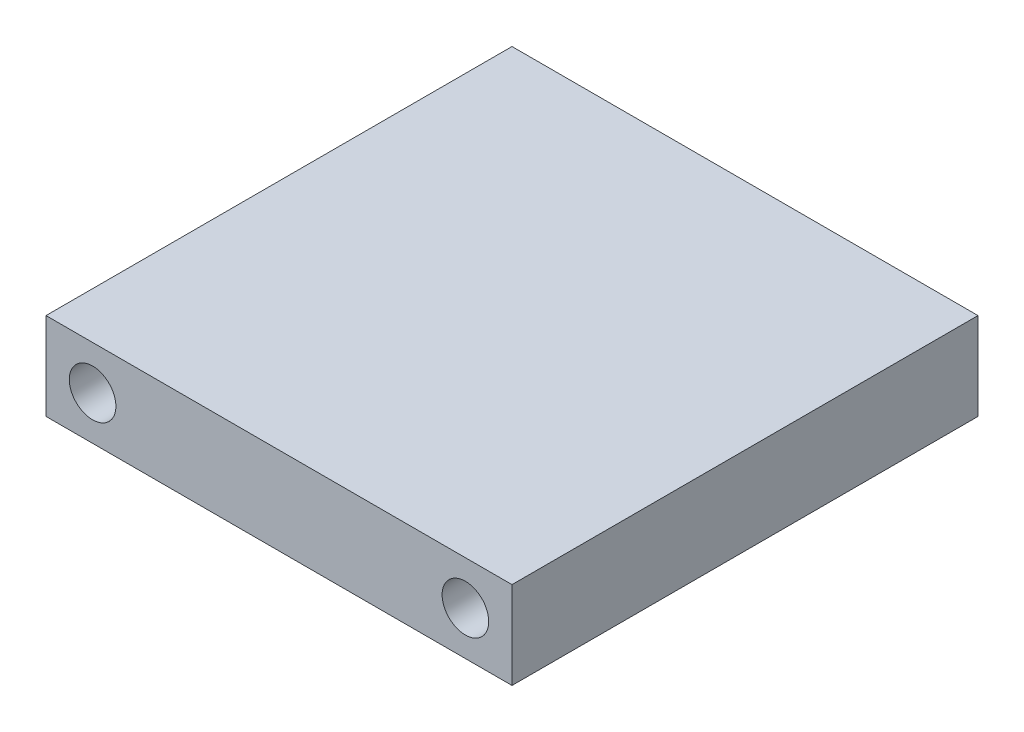
SolidWorks part; units mm, degrees
ref_plane "Front Plane" through (0, 0, 0) normal (0, 0, 1) x (1, 0, 0)
ref_plane "Top Plane" through (0, 0, 0) normal (0, 1, 0) x (1, 0, 0)
ref_plane "Right Plane" through (0, 0, 0) normal (1, 0, 0) x (0, 0, -1)
sketch "Sketch2" plane through (0, 0, 0) normal (0, 1, 0) x (1, 0, 0)
  line L1 (-25.4, 25.4) -> (25.4, 25.4)
  line L2 (-25.4, 25.4) -> (-25.4, -25.4)
  line L3 (-25.4, -25.4) -> (25.4, -25.4)
  line L4 (25.4, 25.4) -> (25.4, -25.4)
  line L5 (-25.4, 25.4) -> (25.4, -25.4) construction
  line L6 (-25.4, -25.4) -> (25.4, 25.4) construction
  point P0 (0, 0)
  dimension "D1" = 50.8
  dimension "D2" = 50.8
extrude "Boss-Extrude1" add sketch "Sketch2" along normal blind 9.525 contours L2 L3 L4 L1
sketch "Sketch3" plane through (0, 0, 25.4) normal (0, 0, 1) x (1, 0, 0)
  line L0 (25.4, 9.525) -> (25.4, 0) construction
  line L1 (-25.4, 9.525) -> (-25.4, 0) construction
  circle A0 centre (20.32, 4.7625) radius 2.54
  circle A1 centre (-20.32, 4.7625) radius 2.54
  point P7 (25.4, 4.7625)
  dimension "D3" = 5.08
  dimension "D1" = 5.08
  dimension "D2" = 5.08
hole_wizard "#6-32 Tapped Hole1" positions "Sketch4" profile "Sketch5" tap size "#6-32" standard "ANSI Inch"
sketch "Sketch4" plane through (0, 0, 25.4) normal (0, 0, 1) x (1, 0, 0)
  circle A0 centre (-20.32, 4.7625) radius 2.54 construction
  circle A1 centre (20.32, 4.7625) radius 2.54 construction
  point P0 (-20.32, 4.7625)
  point P2 (20.32, 4.7625)
sketch "Sketch5" plane through (-20.32, 4.7625, 25.4) normal (1, 0, 0) x (0, -1, 0)
  line L0 (0, 0) -> (0, 10.2107)
  line L1 (0, 10.2107) -> (1.3525, 9.398)
  line L2 (1.3525, 9.398) -> (1.3525, 0)
  line L5 (1.3525, 0) -> (0, 0)
  line L10 (0, 10.2107) -> (-1.3526, 9.398) construction
  line L11 (0, -6.35) -> (0, 107.95) construction
  dimension "Tap Drill Dia." = 2.7051
  dimension "Tap Drill Depth" = 9.398
  dimension "Drill Angle" = 118
cosmetic thread "Hole Thread1" parameters "D1"=7.112, "D2"=3.5052
cosmetic thread "Hole Thread2" parameters "D1"=7.112, "D2"=3.5052
hole_wizard "#6-32 Tapped Hole2" positions "Sketch6" profile "Sketch7" tap size "#6-32" standard "ANSI Inch"
sketch "Sketch6" plane through (0, 0, -25.4) normal (0, 0, -1) x (-1, 0, 0)
  circle A0 centre (-20.32, 4.7625) radius 2.54 construction
  circle A1 centre (20.32, 4.7625) radius 2.54 construction
  point P0 (-20.32, 4.7625)
  point P2 (20.32, 4.7625)
sketch "Sketch7" plane through (20.32, 4.7625, -25.4) normal (1, 0, 0) x (0, 1, 0)
  line L0 (0, 0) -> (0, 10.2107)
  line L1 (0, 10.2107) -> (1.3525, 9.398)
  line L2 (1.3525, 9.398) -> (1.3525, 0)
  line L5 (1.3525, 0) -> (0, 0)
  line L10 (0, 10.2107) -> (-1.3525, 9.398) construction
  line L11 (0, -6.35) -> (0, 107.95) construction
  dimension "Tap Drill Dia." = 2.7051
  dimension "Tap Drill Depth" = 9.398
  dimension "Drill Angle" = 118
cosmetic thread "Hole Thread3" parameters "D1"=7.112, "D2"=3.5052
cosmetic thread "Hole Thread4" parameters "D1"=7.112, "D2"=3.5052
extrude "Cut-Extrude1" cut sketch "Sketch3" against normal through all
